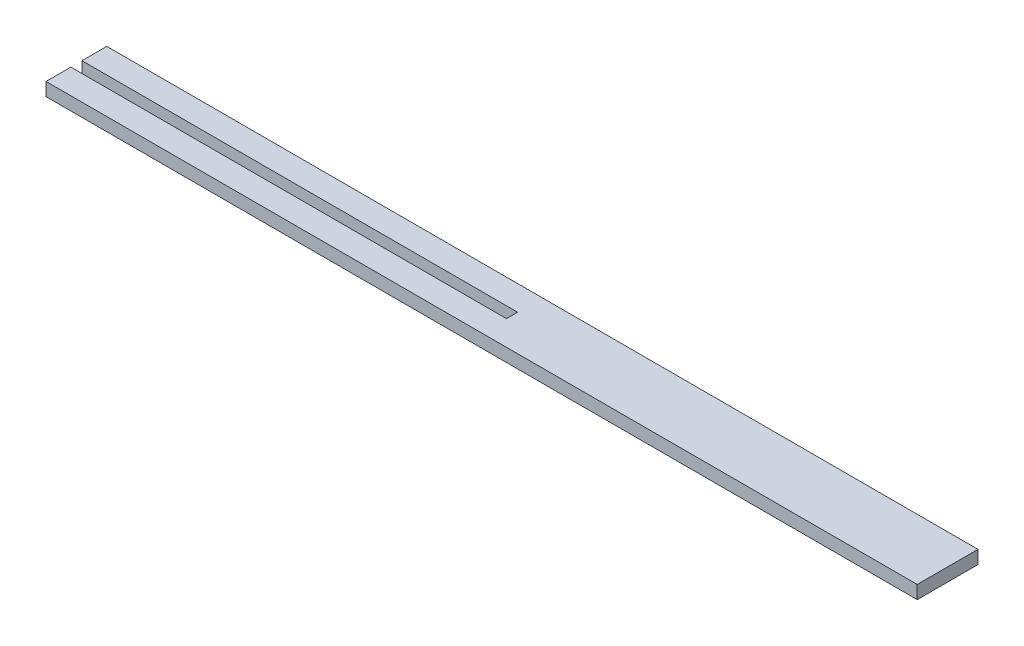
SolidWorks part; units mm, degrees
ref_plane "Front Plane" through (0, 0, 0) normal (0, 0, 1) x (1, 0, 0)
ref_plane "Top Plane" through (0, 0, 0) normal (0, 1, 0) x (1, 0, 0)
ref_plane "Right Plane" through (0, 0, 0) normal (1, 0, 0) x (0, 0, -1)
sketch "Sketch1" plane through (0, 0, 0) normal (0, 1, 0) x (1, 0, 0)
  line L1 (-43, 3) -> (43, 3)
  line L2 (-43, 3) -> (-43, -3)
  line L3 (-43, -3) -> (43, -3)
  line L4 (43, 3) -> (43, -3)
  line L5 (-43, 3) -> (43, -3) construction
  line L6 (-43, -3) -> (43, 3) construction
  point P0 (0, 0)
  dimension "D1" = 86
  dimension "D2" = 6
extrude "Boss-Extrude1" add sketch "Sketch1" along normal blind 1.3
sketch "Sketch2" plane through (0, 1.3, 0) normal (0, 1, 0) x (1, 0, 0)
  line L0 (-43, 3) -> (-43, -3) construction
  line L1 (-43, 0.55) -> (0, 0.55)
  line L2 (-43, 0.55) -> (-43, -0.55)
  line L3 (-43, -0.55) -> (0, -0.55)
  line L4 (0, 0.55) -> (0, -0.55)
  line L5 (0, -55) -> (0, 55) construction
  line L6 (-55, 0) -> (55, 0) construction
  dimension "D1" = 1.1
  dimension "D2" = 0.55
extrude "Cut-Extrude1" cut sketch "Sketch2" against normal blind 1.3
